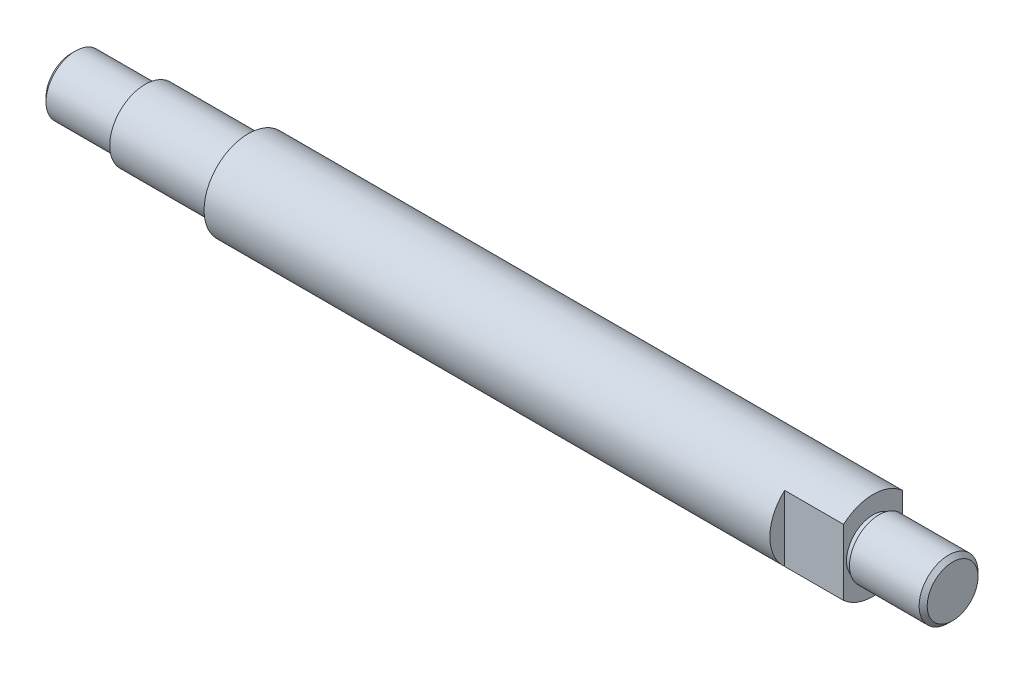
SolidWorks part; units mm, degrees
material "Простая углеродистая сталь"
ref_plane "Спереди" through (0, 0, 0) normal (0, 0, 1) x (1, 0, 0)
ref_plane "Сверху" through (0, 0, 0) normal (0, 1, 0) x (1, 0, 0)
ref_plane "Справа" through (0, 0, 0) normal (1, 0, 0) x (0, 0, -1)
sketch "Эскиз1" plane through (0, 0, 0) normal (0, 0, 1) x (1, 0, 0)
  line L0 (-1007.9786, 0) -> (49390.9535, 0) construction
  line L1 (0, 0) -> (299, 0)
  line L2 (0, 0) -> (0, 10)
  line L3 (0, 10) -> (25, 10)
  line L4 (25, 10) -> (25, 12)
  line L5 (25, 12) -> (60, 12)
  line L6 (60, 12) -> (60, 15)
  line L7 (60, 15) -> (272, 15)
  line L8 (272, 15) -> (272, 9)
  line L9 (272, 9) -> (274, 9)
  line L10 (274, 9) -> (274, 10)
  line L11 (274, 10) -> (299, 10)
  line L12 (299, 10) -> (299, 0)
  dimension "D1" = 299
  dimension "D2" = 10
  dimension "D3" = 25
  dimension "D4" = 2
  dimension "D5" = 35
  dimension "D6" = 3
  dimension "D7" = 212
  dimension "D8" = 2
  dimension "D9" = 6
  dimension "D10" = 10
revolve "Повернуть1" add sketch "Эскиз1" angle 360 about L0
cosmetic thread "Условное изображение резьбы1" parameters "D1"=25, "D2"=17.252
cosmetic thread "Условное изображение резьбы2" parameters "D1"=25, "D2"=17.252
chamfer "Фаска1" distance 1.374 angle 45 2 edges at (299, 0, 10) (0, 0, 10)
sketch "Эскиз2" plane through (0, 0, 0) normal (0, 1, 0) x (1, 0, 0)
  line L0 (-1000, 0) -> (49000, 0) construction
  line L1 (272, 15) -> (60, 15) construction
  line L2 (274, 10) -> (252, 10)
  line L3 (274, 10) -> (274, 15)
  line L4 (274, 15) -> (252, 15)
  line L5 (252, 10) -> (252, 15)
  line L6 (274, -15) -> (252, -15)
  line L7 (252, -10) -> (252, -15)
  line L8 (274, -10) -> (252, -10)
  line L9 (274, -10) -> (274, -15)
  dimension "D1" = 22
extrude "Вырез-Вытянуть1" cut sketch "Эскиз2" against normal mid plane 30
